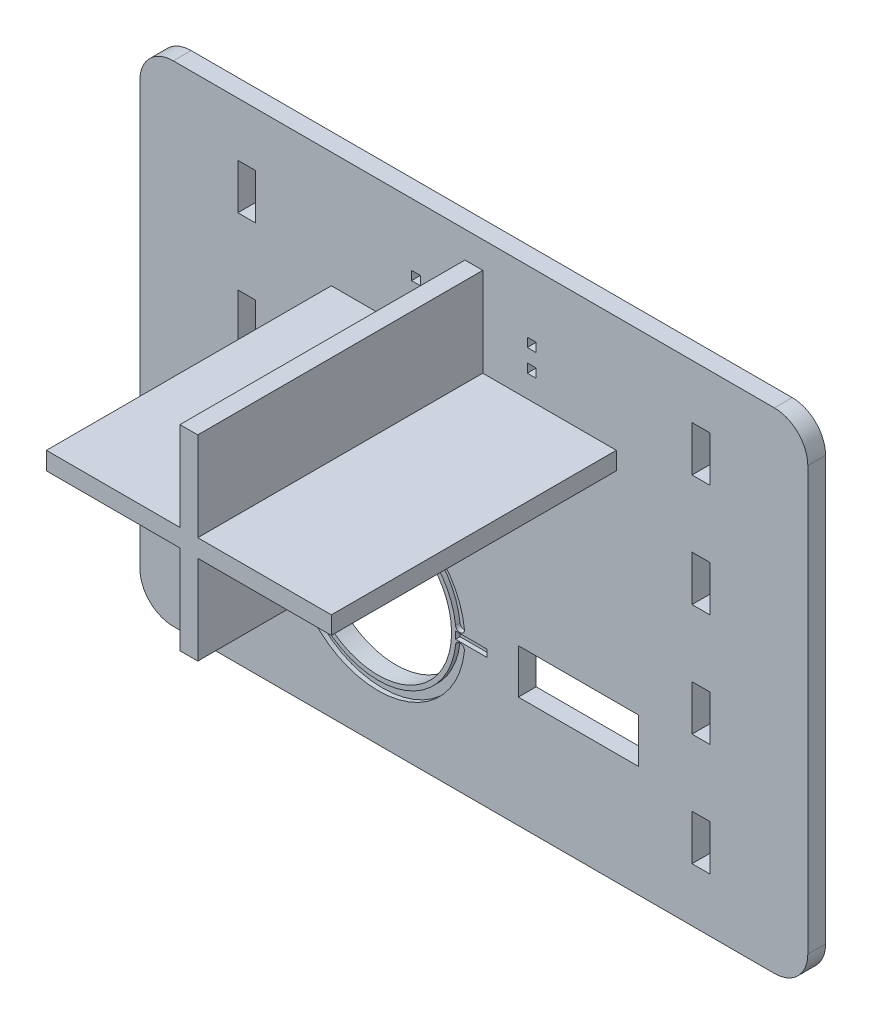
SolidWorks part; units mm, degrees
ref_plane "Alzado" through (0, 0, 0) normal (0, 0, 1) x (1, 0, 0)
ref_plane "Planta" through (0, 0, 0) normal (0, 1, 0) x (1, 0, 0)
ref_plane "Vista lateral" through (0, 0, 0) normal (1, 0, 0) x (0, 0, -1)
sketch "Croquis1" plane through (0, 0, 0) normal (0, 0, 1) x (1, 0, 0)
  line L0 (75, 90) -> (75, 0) construction
  line L1 (7.5, 0) -> (142.5, 0)
  line L2 (0, 7.5) -> (0, 102.5)
  line L3 (7.5, 110) -> (142.5, 110)
  line L4 (150, 7.5) -> (150, 102.5)
  line L5 (0, 55) -> (150, 55) construction
  arc A0 (7.5, 110) -> (0, 102.5) centre (7.5, 102.5) ccw
  arc A1 (142.5, 110) -> (150, 102.5) centre (142.5, 102.5) cw
  arc A2 (142.5, 0) -> (150, 7.5) centre (142.5, 7.5) ccw
  arc A3 (7.5, 0) -> (0, 7.5) centre (7.5, 7.5) cw
  dimension "D3" = 7.5
  dimension "D4" = 7.5
  dimension "D1" = 110
  dimension "D2" = 150
  dimension "D5" = 7.5
extrude "Saliente-Extruir1" add sketch "Croquis1" along normal blind 4
sketch "Croquis2" plane through (0, 0, 4) normal (0, 0, 1) x (1, 0, 0)
  line L0 (75, 90) -> (75, 0) construction
  line L1 (85, 25) -> (112, 25)
  line L2 (85, 25) -> (85, 35)
  line L3 (85, 35) -> (112, 35)
  line L4 (112, 25) -> (112, 35)
  line L5 (85, 25) -> (112, 35) construction
  line L6 (85, 35) -> (112, 25) construction
  line L9 (0, 55) -> (150, 55) construction
  circle A0 centre (53.5, 30) radius 16.5
  point P0 (107.9685, 43.4666)
  dimension "D5" = 33
  dimension "D7" = 21.5
  dimension "D1" = 10
  dimension "D2" = 27
  dimension "D3" = 10
  dimension "D4" = 20
  dimension "D6" = 25
extrude "Cortar-Extruir1" cut sketch "Croquis2" against normal blind 4
sketch "Croquis4" plane through (0, 0, 4) normal (0, 0, 1) x (1, 0, 0)
  line L0 (73, 60) -> (73, 80)
  line L7 (77, 60) -> (73, 60)
  line L8 (73, 80) -> (43, 80)
  line L9 (43, 80) -> (43, 84)
  line L10 (43, 84) -> (73, 84)
  line L11 (73, 84) -> (73, 104)
  line L12 (75, 90) -> (75, 0) construction
  line L13 (73, 104) -> (77, 104)
  line L15 (75, 87.4066) -> (75, 66.8669) construction
  line L16 (77, 84) -> (77, 104)
  line L17 (107, 84) -> (77, 84)
  line L18 (107, 80) -> (107, 84)
  line L19 (77, 80) -> (107, 80)
  line L20 (77, 60) -> (77, 80)
  line L21 (0, 55) -> (150, 55) construction
  point P5 (75, 104)
  point P18 (75, 60)
  dimension "D1" = 4
  dimension "D2" = 4
  dimension "D3" = 30
  dimension "D4" = 20
  dimension "D5" = 5
extrude "Saliente-Extruir2" add sketch "Croquis4" along normal blind 64
sketch "Croquis5" plane through (0, 0, 0) normal (0, 0, -1) x (-1, 0, 0)
  line L0 (-128, 62.5) -> (-124, 62.5)
  line L1 (-124, 62.5) -> (-124, 72.7)
  line L2 (-124, 72.7) -> (-128, 72.7)
  line L3 (-128, 72.7) -> (-128, 62.5)
  line L4 (-128, 47.5) -> (-124, 47.5)
  line L5 (-124, 47.5) -> (-124, 37.3)
  line L6 (-124, 37.3) -> (-128, 37.3)
  line L7 (-128, 37.3) -> (-128, 47.5)
  line L8 (-128, 22.3) -> (-124, 22.3)
  line L9 (-124, 22.3) -> (-124, 12.1)
  line L10 (-124, 12.1) -> (-128, 12.1)
  line L11 (-128, 12.1) -> (-128, 22.3)
  line L12 (-128, 97.9) -> (-124, 97.9)
  line L13 (-124, 97.9) -> (-124, 87.7)
  line L14 (-124, 87.7) -> (-128, 87.7)
  line L15 (-128, 87.7) -> (-128, 97.9)
  line L16 (-75, 54.3479) -> (-75, 69.6327) construction
  line L17 (-26, 87.7) -> (-22, 87.7)
  line L18 (-26, 97.9) -> (-26, 87.7)
  line L19 (-22, 97.9) -> (-26, 97.9)
  line L20 (-22, 87.7) -> (-22, 97.9)
  line L21 (-26, 72.7) -> (-22, 72.7)
  line L22 (-26, 62.5) -> (-26, 72.7)
  line L23 (-22, 62.5) -> (-26, 62.5)
  line L24 (-22, 72.7) -> (-22, 62.5)
  line L25 (-26, 37.3) -> (-22, 37.3)
  line L26 (-26, 47.5) -> (-26, 37.3)
  line L27 (-22, 47.5) -> (-26, 47.5)
  line L28 (-22, 37.3) -> (-22, 47.5)
  line L29 (-26, 12.1) -> (-22, 12.1)
  line L30 (-26, 22.3) -> (-26, 12.1)
  line L31 (-22, 22.3) -> (-26, 22.3)
  line L32 (-22, 12.1) -> (-22, 22.3)
  line L33 (-75, 83.7955) -> (-75, 101.1381) construction
  line L34 (-75, 90) -> (-75, 0) construction
  line L35 (-129.3168, 55) -> (-25.894, 55) construction
  line L36 (0, 55) -> (-150, 55) construction
  line L37 (-43, 82) -> (-107, 82) construction
  line L38 (-87, 96) -> (-89, 96)
  line L39 (-87, 96) -> (-87, 94)
  line L40 (-87, 94) -> (-89, 94)
  line L41 (-89, 96) -> (-89, 94)
  line L42 (-87, 91) -> (-89, 91)
  line L43 (-87, 91) -> (-87, 89)
  line L44 (-87, 89) -> (-89, 89)
  line L45 (-89, 91) -> (-89, 89)
  line L46 (-43, 84) -> (-43, 80) construction
  line L47 (-107, 80) -> (-107, 84) construction
  line L48 (-107, 84) -> (-77, 84) construction
  line L49 (-61, 91) -> (-61, 89)
  line L50 (-63, 89) -> (-61, 89)
  line L51 (-63, 91) -> (-63, 89)
  line L52 (-63, 91) -> (-61, 91)
  line L53 (-61, 96) -> (-61, 94)
  line L54 (-63, 94) -> (-61, 94)
  line L55 (-63, 96) -> (-63, 94)
  line L56 (-63, 96) -> (-61, 96)
  line L57 (-89, 73) -> (-89, 75)
  line L58 (-87, 75) -> (-89, 75)
  line L59 (-87, 73) -> (-87, 75)
  line L60 (-87, 73) -> (-89, 73)
  line L61 (-89, 68) -> (-89, 70)
  line L62 (-87, 70) -> (-89, 70)
  line L63 (-87, 68) -> (-87, 70)
  line L64 (-87, 68) -> (-89, 68)
  line L65 (-63, 68) -> (-61, 68)
  line L66 (-63, 68) -> (-63, 70)
  line L67 (-63, 70) -> (-61, 70)
  line L68 (-61, 68) -> (-61, 70)
  line L69 (-63, 73) -> (-61, 73)
  line L70 (-63, 73) -> (-63, 75)
  line L71 (-63, 75) -> (-61, 75)
  line L72 (-61, 73) -> (-61, 75)
  point P43 (-126, 87.7)
  point P45 (-124, 67.6)
  point P53 (-87, 95)
  dimension "D1" = 10.2
  dimension "D2" = 4
  dimension "D3" = 15
  dimension "D4" = 15
  dimension "D5" = 15
  dimension "D6" = 7.5
  dimension "D7" = 49
  dimension "D8" = 2
  dimension "D9" = 12
  dimension "D10" = 3
  dimension "D11" = 5
extrude "Cortar-Extruir2" cut sketch "Croquis5" against normal up to next
sketch "Croquis6" plane through (0, 0, 4) normal (0, 0, 1) x (1, 0, 0)
  line L0 (53.5, 30) -> (53.5, 14.0701) construction
  line L1 (53.5, 30) -> (37, 30) construction
  line L2 (70.9, 30.8059) -> (70.9, 29.1941)
  line L3 (29.1, 30.8059) -> (36.1, 30.8059)
  line L4 (29.1, 30.8059) -> (29.1, 29.1941)
  line L5 (29.1, 29.1941) -> (36.1, 29.1941)
  line L6 (36.1, 30.8059) -> (36.1, 29.1941)
  line L7 (77.9, 29.1941) -> (70.9, 29.1941)
  line L8 (77.9, 30.8059) -> (77.9, 29.1941)
  line L9 (77.9, 30.8059) -> (70.9, 30.8059)
  arc A0 (71.8916, 32) -> (35.1084, 32) centre (53.5, 30) ccw construction
  arc A1 (72.8857, 32.1081) -> (34.1143, 32.1081) centre (53.5, 30) ccw
  arc A2 (70.8974, 31.8919) -> (36.1026, 31.8919) centre (53.5, 30) ccw
  arc A3 (70.8974, 31.8919) -> (72.8857, 32.1081) centre (71.8916, 32) ccw
  arc A4 (34.1143, 32.1081) -> (36.1026, 31.8919) centre (35.1084, 32) ccw
  circle A5 centre (53.5, 30) radius 16.5 construction
  arc A6 (71.8916, 28) -> (35.1084, 28) centre (53.5, 30) cw construction
  arc A7 (72.8857, 27.8919) -> (34.1143, 27.8919) centre (53.5, 30) cw
  arc A8 (70.8974, 28.1081) -> (36.1026, 28.1081) centre (53.5, 30) cw
  arc A9 (70.8974, 28.1081) -> (72.8857, 27.8919) centre (71.8916, 28) cw
  arc A10 (34.1143, 27.8919) -> (36.1026, 28.1081) centre (35.1084, 28) cw
  point P4 (53.5, 48.5)
  point P16 (53.5, 11.5)
  point P25 (35.0003, 31.0059)
  point P26 (35.0003, 28.9941)
  dimension "D1" = 17.5
  dimension "D2" = 19.5
  dimension "D3" = 2
  dimension "D4" = 2
  dimension "D5" = 0.2
  dimension "D6" = 0.2
  dimension "D7" = 0.9
  dimension "D8" = 7
extrude "Cortar-Extruir3" cut sketch "Croquis6" against normal blind 1
ref_plane "Plano1" through (0, 0, 2) normal (0, 0, 1) x (1, 0, 0)
mirror "Simetría1" about plane through (0, 0, 2) normal (0, 0, 1) of "Cortar-Extruir3"
